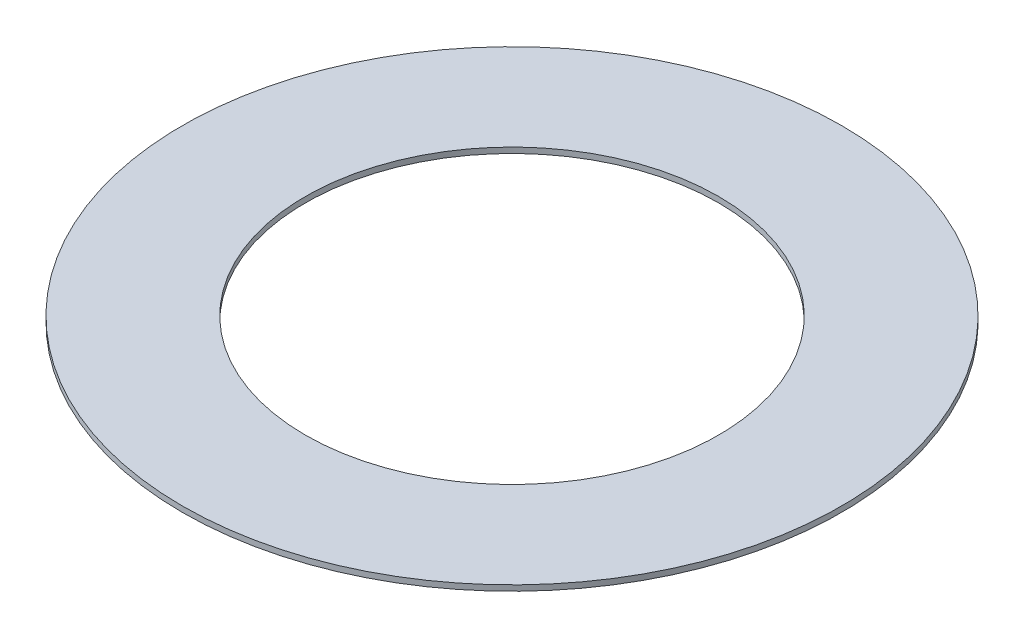
SolidWorks part; units mm, degrees
ref_plane "Front Plane" through (0, 0, 0) normal (0, 0, 1) x (1, 0, 0)
ref_plane "Top Plane" through (0, 0, 0) normal (0, 1, 0) x (1, 0, 0)
ref_plane "Right Plane" through (0, 0, 0) normal (1, 0, 0) x (0, 0, -1)
sketch "Sketch1" plane through (0, 0, 0) normal (0, 1, 0) x (1, 0, 0)
  circle A0 centre (0, 0) radius 29.5
extrude "Boss-Extrude1" add sketch "Sketch1" along normal blind 0.5
sketch "Sketch2" plane through (0, 0, 0) normal (0, -1, 0) x (1, 0, 0)
  circle A0 centre (0, 0) radius 18.5
extrude "Cut-Extrude1" cut sketch "Sketch2" against normal through all
